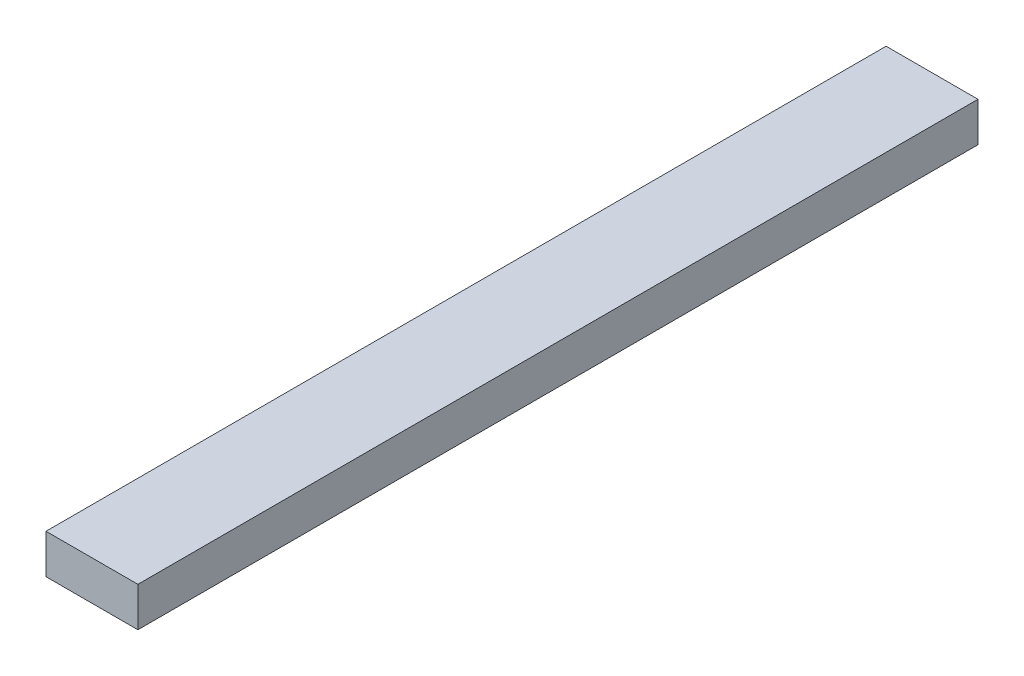
SolidWorks part; units mm, degrees
material "Pine"
ref_plane "Front Plane" through (0, 0, 0) normal (0, 0, 1) x (1, 0, 0)
ref_plane "Top Plane" through (0, 0, 0) normal (0, 1, 0) x (1, 0, 0)
ref_plane "Right Plane" through (0, 0, 0) normal (1, 0, 0) x (0, 0, -1)
sketch "Sketch1" plane through (0, 0, 0) normal (0, 0, 1) x (1, 0, 0)
  line L1 (0, 0) -> (88.9, 0)
  line L2 (0, 0) -> (0, 38.1)
  line L3 (0, 38.1) -> (88.9, 38.1)
  line L4 (88.9, 0) -> (88.9, 38.1)
  dimension "D1" = 88.9
  dimension "D2" = 38.1
extrude "Boss-Extrude1" add sketch "Sketch1" along normal blind 812.8
sketch "Sketch2" plane through (0, 0, 0) normal (0, 0, -1) x (-1, 0, 0)
  line L1 (-88.9, 0) -> (-88.9, 38.1) construction
  line L2 (0, 38.1) -> (0, 0) construction
  line L3 (-44.45, 19.05) -> (-88.9, 19.05) construction
  line L4 (-44.45, 19.05) -> (0, 19.05) construction
  circle A0 centre (-66.675, 19.05) radius 0.8763
  circle A1 centre (-22.225, 19.05) radius 0.8763
  dimension "D1" = 1.7526
sketch "Sketch3" plane through (0, 0, 0) normal (0, -1, 0) x (1, 0, 0)
  line L0 (44.45, 812.8) -> (44.45, 768.35) construction
  line L1 (0, 812.8) -> (88.9, 812.8) construction
  line L2 (44.45, 768.35) -> (44.45, 723.9) construction
  line L3 (88.9, 406.4) -> (0, 406.4) construction
  line L4 (88.9, 812.8) -> (88.9, 0) construction
  line L5 (0, 812.8) -> (0, 0) construction
  line L6 (44.45, 406.4) -> (44.45, 450.85) construction
  line L7 (44.45, 406.4) -> (44.45, 361.95) construction
  circle A0 centre (44.45, 790.575) radius 0.8763
  circle A1 centre (44.45, 746.125) radius 0.8763
  circle A2 centre (44.45, 22.225) radius 0.8763
  circle A3 centre (44.45, 66.675) radius 0.8763
  circle A4 centre (44.45, 384.175) radius 0.8763
  circle A5 centre (44.45, 428.625) radius 0.8763
  dimension "D2" = 1.7526
  dimension "D4" = 1.7526
  dimension "D1" = 88.9
  dimension "D3" = 88.9
equation "\"length\"= 20"
equation "\"length\"= 22"
equation "\"length\"= 36"
equation "\"length\"= 26"
equation "\"length\"= 27"
equation "\"length\"= 28"
equation "\"length\"= 39"
equation "\"length\"= 96"
equation "\"length\"= 30"
equation "\"length\"= 32"
